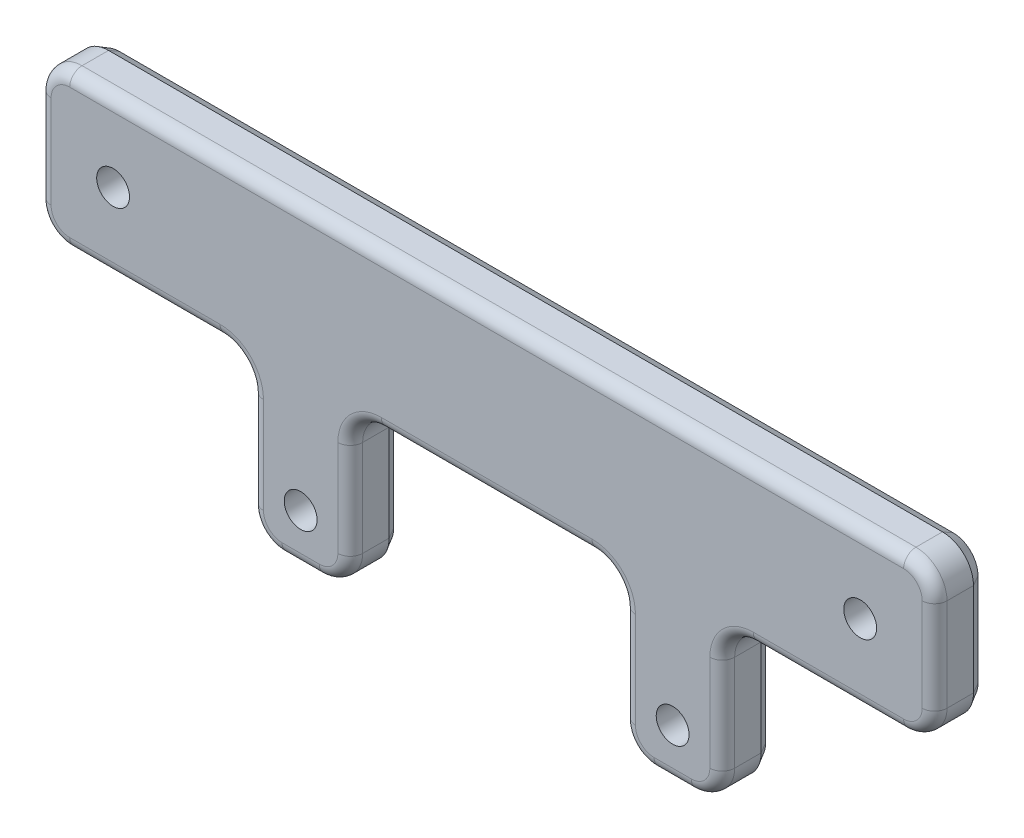
SolidWorks part; units mm, degrees
ref_plane "Front Plane" through (0, 0, 0) normal (0, 0, 1) x (1, 0, 0)
ref_plane "Top Plane" through (0, 0, 0) normal (0, 1, 0) x (1, 0, 0)
ref_plane "Right Plane" through (0, 0, 0) normal (1, 0, 0) x (0, 0, -1)
sketch "Sketch2" plane through (0, 0, 0) normal (0, 0, 1) x (1, 0, 0)
  line L1 (-72.25, -12.5) -> (72.25, -12.5)
  line L2 (-72.25, -12.5) -> (-72.25, 12.5)
  line L3 (-72.25, 12.5) -> (72.25, 12.5)
  line L4 (72.25, -12.5) -> (72.25, 12.5)
  line L5 (-72.25, -12.5) -> (72.25, 12.5) construction
  line L6 (-72.25, 12.5) -> (72.25, -12.5) construction
  point P0 (0, 0)
  dimension "D1" = 144.5
  dimension "D2" = 25
extrude "Boss-Extrude1" add sketch "Sketch2" along normal blind 8
sketch "Sketch3" plane through (0, 0, 8) normal (0, 0, 1) x (1, 0, 0)
  line L0 (-72.25, 12.5) -> (-72.25, -12.5) construction
  line L1 (-60.25, 0) -> (60.25, 0) construction
  circle A0 centre (-60.25, 0) radius 2.65
  circle A1 centre (60.25, 0) radius 2.65
  point P4 (0, 0)
  point P11 (-72.25, 0)
  dimension "D1" = 5.3
  dimension "D4" = 120.5
extrude "Cut-Extrude1" cut sketch "Sketch3" against normal through all
sketch "Sketch5" plane through (0, 0, 8) normal (0, 0, 1) x (1, 0, 0)
  line L0 (-72.25, -12.5) -> (72.25, -12.5) construction
  line L1 (-38, -12.5) -> (-22, -12.5)
  line L2 (-38, -12.5) -> (-38, -38)
  line L3 (-38, -38) -> (-22, -38)
  line L4 (-22, -12.5) -> (-22, -38)
  line L5 (60.25, 0) -> (-60.25, 0) construction
  line L10 (0, 0) -> (0, -29.3478) construction
  line L11 (38, -38) -> (22, -38)
  line L12 (22, -12.5) -> (22, -38)
  line L13 (38, -12.5) -> (22, -12.5)
  line L14 (38, -12.5) -> (38, -38)
  circle A0 centre (-30, -30) radius 2.65
  circle A1 centre (-60.25, 0) radius 2.65 construction
  circle A2 centre (30, -30) radius 2.65
  point P9 (-30, -38)
  point P15 (0, 0)
  dimension "D1" = 30
  dimension "D2" = 8
  dimension "D3" = 16
  dimension "D4" = 30
extrude "Boss-Extrude2" add sketch "Sketch5" against normal up to surface (8 mm away) up to face at (-57.6, 0, 0)
fillet "Fillet1" radius 5 12 edges at (-72.25, -12.5, 4) (-72.25, 12.5, 4) (72.25, -12.5, 4) (72.25, 12.5, 4) (38, -12.5, 4) (38, -38, 4) (22, -38, 4) (22, -12.5, 4) (-38, -12.5, 4) (-22, -12.5, 4) (-38, -38, 4) (-22, -38, 4)
fillet "Fillet2" radius 2 24 edges at (70.7855, 11.0355, 8) (72.25, 0, 8) (70.7855, -11.0355, 8) (55.125, -12.5, 8) (-55.125, -12.5, 8) (-70.7855, -11.0355, 8) (-72.25, 0, 8) (-70.7855, 11.0355, 8) (0, 12.5, 8) (39.4645, -13.9645, 8) (38, -25.25, 8) (36.5355, -36.5355, 8) (30, -38, 8) (23.4645, -36.5355, 8) (22, -25.25, 8) (20.5355, -13.9645, 8) (0, -12.5, 8) (-20.5355, -13.9645, 8) (-22, -25.25, 8) (-23.4645, -36.5355, 8) (-30, -38, 8) (-36.5355, -36.5355, 8) (-38, -25.25, 8) (-39.4645, -13.9645, 8)
chamfer "Chamfer1" distance 1 angle 60 24 edges at (0, 12.5, 0) (-70.7855, 11.0355, 0) (70.7855, 11.0355, 0) (-72.25, 0, 0) (72.25, 0, 0) (-70.7855, -11.0355, 0) (70.7855, -11.0355, 0) (-55.125, -12.5, 0) (55.125, -12.5, 0) (30, -38, 0) (36.5355, -36.5355, 0) (23.4645, -36.5355, 0) (38, -25.25, 0) (22, -25.25, 0) (39.4645, -13.9645, 0) (20.5355, -13.9645, 0) (0, -12.5, 0) (-20.5355, -13.9645, 0) (-22, -25.25, 0) (-23.4645, -36.5355, 0) (-30, -38, 0) (-36.5355, -36.5355, 0) (-38, -25.25, 0) (-39.4645, -13.9645, 0)
chamfer "Chamfer2" distance 1 angle 30 4 edges at (62.9, 0, 0) (-57.6, 0, 0) (-32.65, -30, 0) (27.35, -30, 0)
